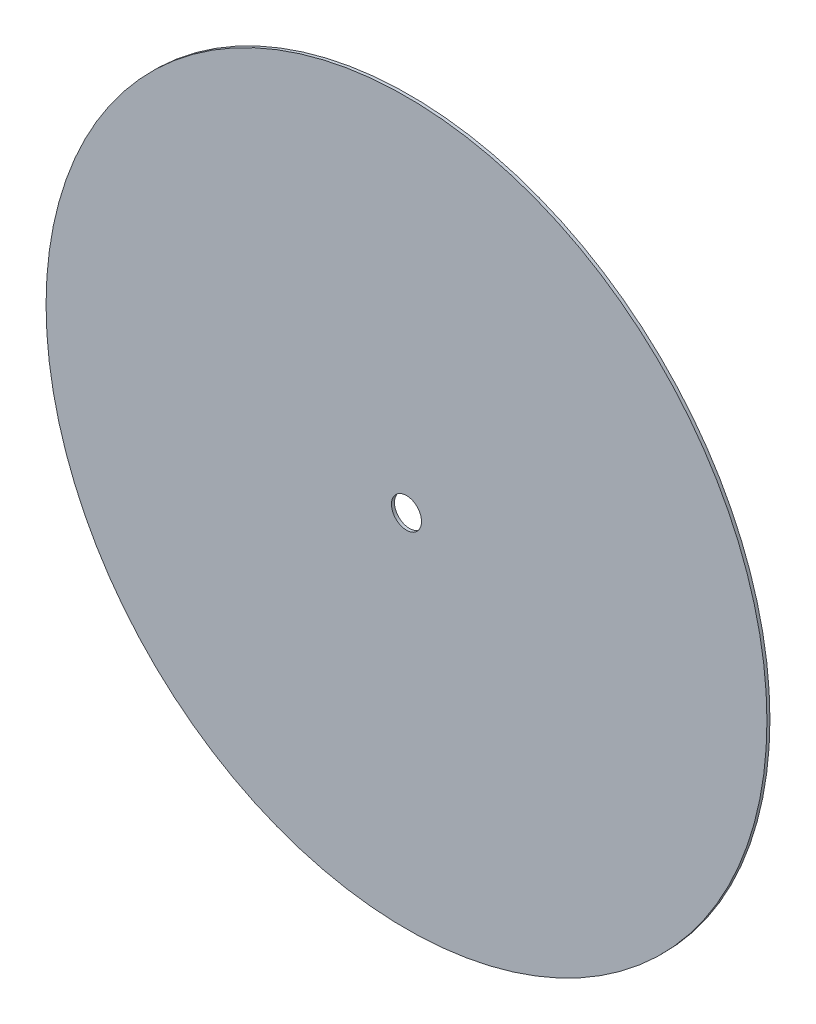
SolidWorks part; units mm, degrees
ref_plane "Front Plane" through (0, 0, 0) normal (0, 0, 1) x (1, 0, 0)
ref_plane "Top Plane" through (0, 0, 0) normal (0, 1, 0) x (1, 0, 0)
ref_plane "Right Plane" through (0, 0, 0) normal (1, 0, 0) x (0, 0, -1)
sketch "Sketch1" plane through (0, 0, 0) normal (0, 0, 1) x (1, 0, 0)
  circle A0 centre (0, 0) radius 152.4
  dimension "D1" = 304.8
extrude "Boss-Extrude1" add sketch "Sketch1" along normal blind 1.27
sketch "Sketch2" plane through (0, 0, 1.27) normal (0, 0, 1) x (1, 0, 0)
  circle A0 centre (0, 0) radius 6.35
  dimension "D1" = 12.7
extrude "Cut-Extrude1" cut sketch "Sketch2" against normal through all
